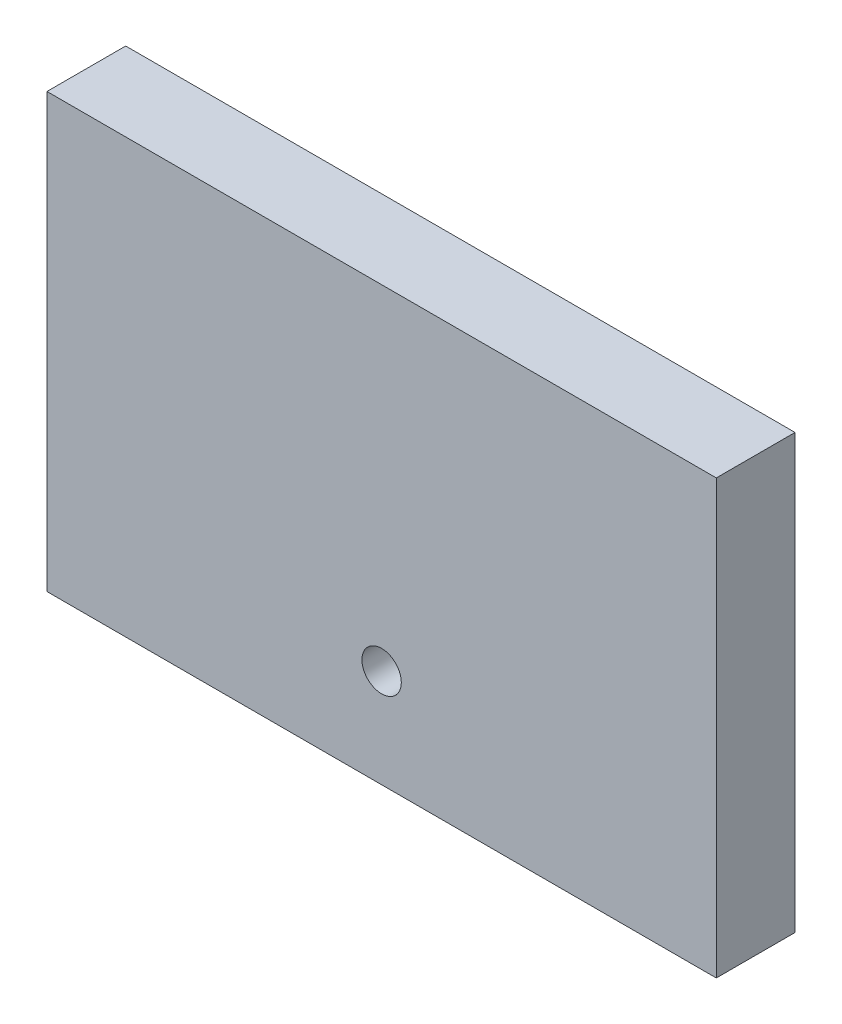
SolidWorks part; units mm, degrees
material "PLA imprimante 3D"
ref_plane "Plan de face" through (0, 0, 0) normal (0, 0, 1) x (1, 0, 0)
ref_plane "Plan de dessus" through (0, 0, 0) normal (0, 1, 0) x (1, 0, 0)
ref_plane "Plan de droite" through (0, 0, 0) normal (1, 0, 0) x (0, 0, -1)
sketch "Esquisse1" plane through (0, 0, 0) normal (0, 0, 1) x (1, 0, 0)
  line L1 (0, 0) -> (17, 0)
  line L2 (0, 0) -> (0, -11)
  line L3 (0, -11) -> (17, -11)
  line L4 (17, 0) -> (17, -11)
  dimension "D1" = 17
  dimension "D2" = 11
extrude "Boss.-Extru.1" add sketch "Esquisse1" along normal blind 2
sketch "Esquisse2" plane through (0, 0, 2) normal (0, 0, 1) x (1, 0, 0)
  line L0 (0, -5.5) -> (23.0612, -5.5) construction
  line L1 (0, 0) -> (0, -11) construction
  line L2 (8.5, 0) -> (8.5, -12.6237) construction
  line L3 (17, 0) -> (0, 0) construction
  circle A1 centre (8.5, -8.5) radius 0.5
  dimension "D1" = 1
  dimension "D2" = 3
extrude "Enlèv. mat.-Extru.2" cut sketch "Esquisse2" against normal blind 2
